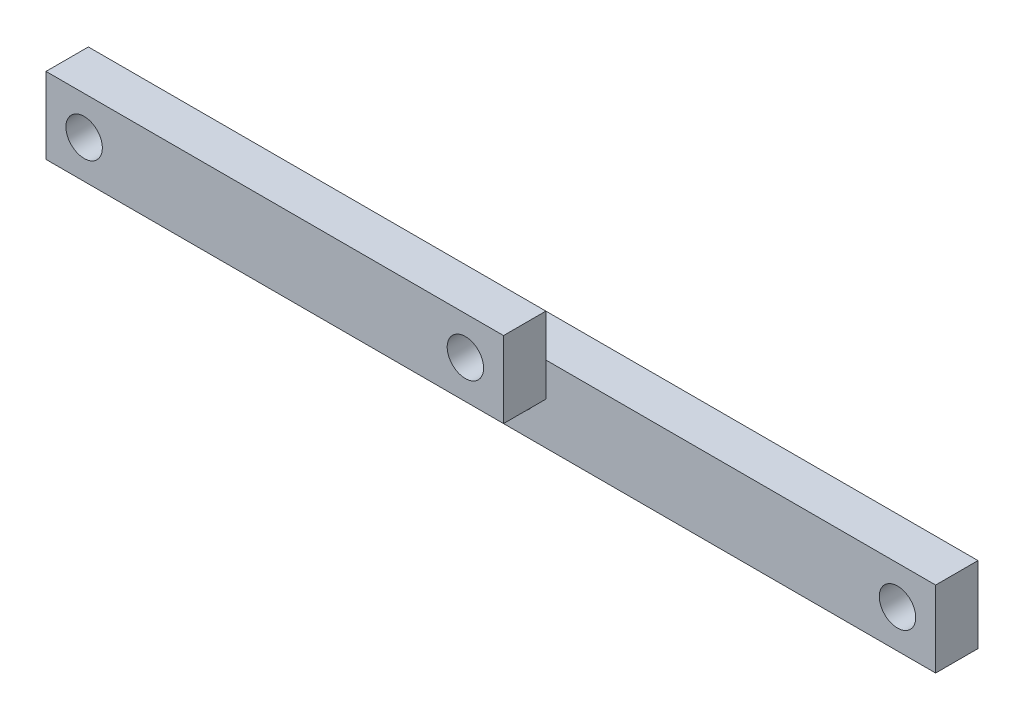
SolidWorks part; units mm, degrees
ref_plane "Front Plane" through (0, 0, 0) normal (0, 0, 1) x (1, 0, 0)
ref_plane "Top Plane" through (0, 0, 0) normal (0, 1, 0) x (1, 0, 0)
ref_plane "Right Plane" through (0, 0, 0) normal (1, 0, 0) x (0, 0, -1)
sketch "Sketch1" plane through (0, 0, 0) normal (0, 0, 1) x (1, 0, 0)
  line L1 (-27, -4.5) -> (27, -4.5)
  line L2 (-27, -4.5) -> (-27, 4.5)
  line L3 (-27, 4.5) -> (27, 4.5)
  line L4 (27, -4.5) -> (27, 4.5)
  line L5 (-27, -4.5) -> (27, 4.5) construction
  line L6 (-27, 4.5) -> (27, -4.5) construction
  point P0 (0, 0)
  point P5 (-24.4895, 33.8939)
  point P11 (-33.519, 27.3726)
  point P12 (6.1105, 28.543)
  point P13 (4.7728, 38.0742)
  point P15 (27.3466, 0)
  point P16 (35.2056, 0)
  point P17 (0, 0)
  dimension "D2" = 54
  dimension "D4" = 9
  dimension "D6" = 0
  dimension "D7" = 0
other "AlignGroup1"
extrude "Boss-Extrude3" add sketch "Sketch1" along normal blind 5 contours L3 L4 L1 L2
sketch3d "3DSketch2" plane through (0, 0, 0) normal (0, 0, 1) x (1, 0, 0)
  dimension "D1" = 51
sketch "Sketch2" plane through (0, 0, -51) normal (0, 0, -1) x (-1, 0, 0)
  line L1 (-27, -46.5) -> (27, -46.5)
  line L2 (-27, -46.5) -> (-27, -55.5)
  line L3 (-27, -55.5) -> (27, -55.5)
  line L4 (27, -46.5) -> (27, -55.5)
  line L5 (-27, -46.5) -> (27, -55.5) construction
  line L6 (-27, -55.5) -> (27, -46.5) construction
  point P0 (0, -51)
  point P5 (2.6821, -30.4926)
  point P7 (7.5011, -31.3129)
  point P8 (0, 0)
  dimension "D1" = 54
  dimension "D2" = 9
  dimension "D3" = 51
  dimension "D4" = 0
extrude "Boss-Extrude4" add sketch "Sketch2" against normal blind 5 separate body
sketch "Sketch3" plane through (0, 0, 5) normal (0, 0, 1) x (1, 0, 0)
  circle A0 centre (22.5, 0) radius 2.15
  circle A1 centre (-22.5, 0) radius 2.15
  circle A2 centre (-22.5, -51) radius 2.15
  circle A3 centre (22.5, -51) radius 2.15
  point P8 (-17.2812, 0)
  point P10 (29.2238, -51)
  point P11 (-15.5412, 0)
  point P12 (-18.7048, 0)
  point P13 (21.9073, -7.2793)
  dimension "D1" = 4.3
  dimension "D2" = 4.3
  dimension "D3" = 4.3
  dimension "D4" = 4.3
  dimension "D5" = 51
  dimension "D6" = 0
  dimension "D7" = 45
  dimension "D8" = 51
  dimension "D9" = 45
  dimension "D10" = 0
  dimension "D11" = 22.5
  dimension "D12" = 0
extrude "Cut-Extrude1" cut sketch "Sketch3" against normal through all both and the other way through all
